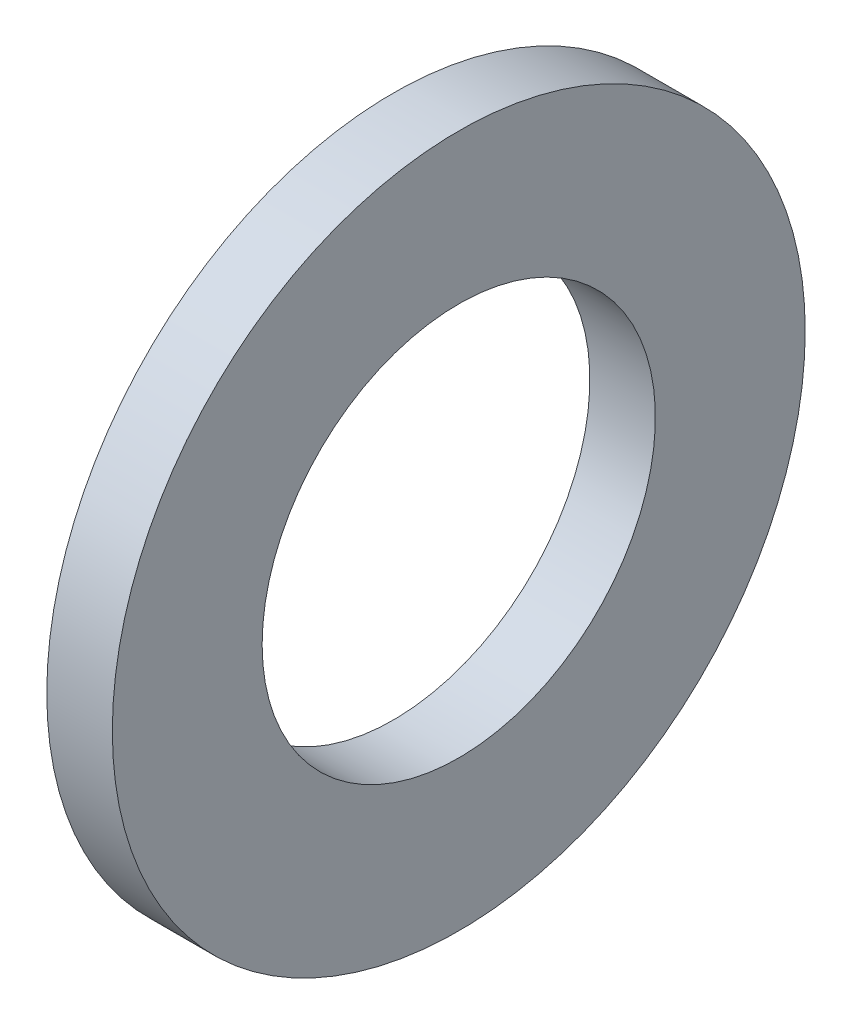
SolidWorks part; units mm, degrees
ref_plane "Plane1" through (0, 0, 0) normal (0, 0, 1) x (1, 0, 0)
ref_plane "Plane2" through (0, 0, 0) normal (0, 1, 0) x (1, 0, 0)
ref_plane "Plane3" through (0, 0, 0) normal (1, 0, 0) x (0, 0, -1)
sketch "Sketch1" plane through (0, 0, 0) normal (0, 0, 1) x (1, 0, 0)
  line L0 (-34.925, 0) -> (9.525, 0) construction
  line L1 (0, 10.5) -> (0, 18.5)
  line L2 (0, 18.5) -> (-3.5, 18.5)
  line L3 (-3.5, 18.5) -> (-3.5, 10.5)
  line L4 (-3.5, 10.5) -> (0, 10.5)
  dimension "Thickness" = 3.5
  dimension "Inside_dia" = 21
  dimension "Outside_dia" = 37
revolve "Base-Revolve" add sketch "Sketch1" angle 360 about L0
